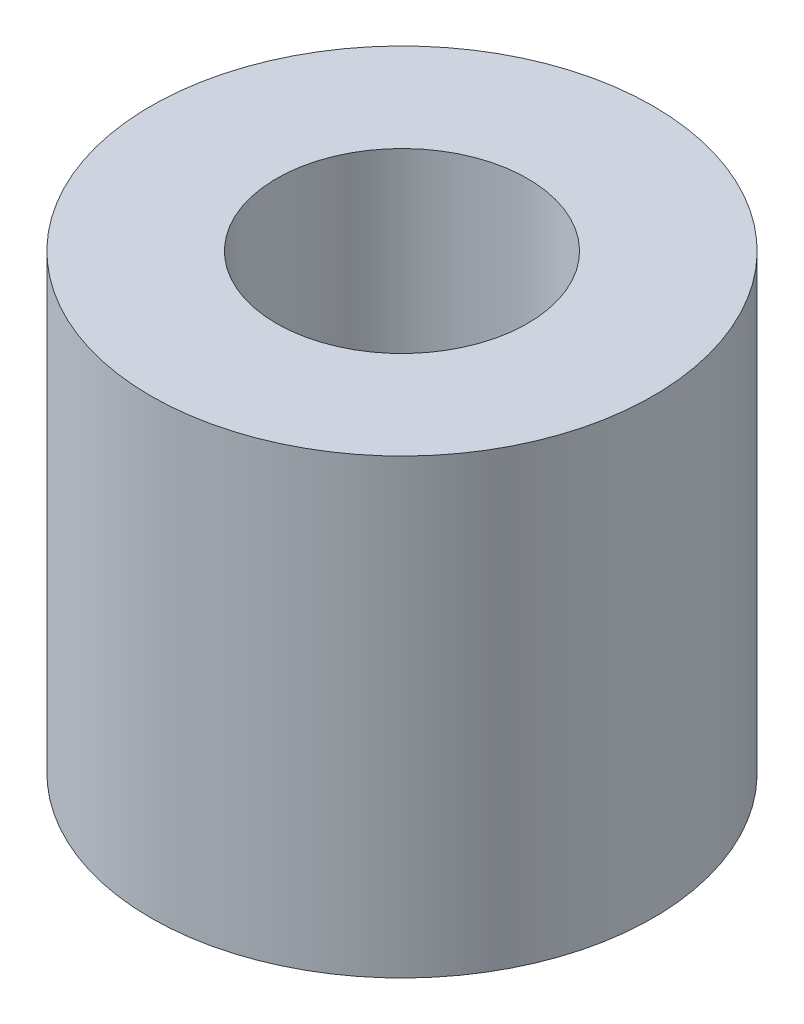
SolidWorks part; units mm, degrees
material "Stainless Steel (ferritic)"
ref_plane "Front Plane" through (0, 0, 0) normal (0, 0, 1) x (1, 0, 0)
ref_plane "Top Plane" through (0, 0, 0) normal (0, 1, 0) x (1, 0, 0)
ref_plane "Right Plane" through (0, 0, 0) normal (1, 0, 0) x (0, 0, -1)
sketch "Sketch1" plane through (0, 0, 0) normal (0, 1, 0) x (1, 0, 0)
  circle A0 centre (0, 0) radius 2.5
  circle A1 centre (0, 0) radius 5
  dimension "D1" = 10
  dimension "D2" = 5
extrude "Boss-Extrude1" add sketch "Sketch1" along normal blind 9
